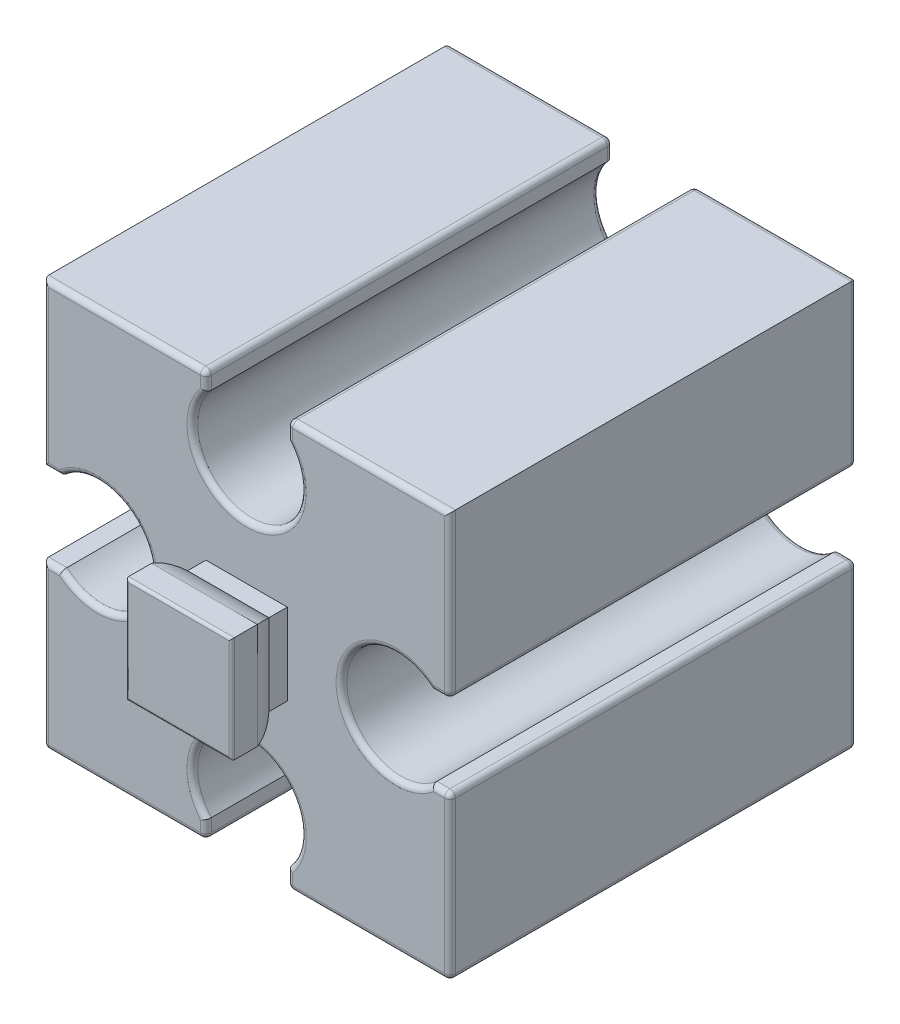
SolidWorks part; units mm, degrees
ref_plane "前视基准面" through (0, 0, 0) normal (0, 0, 1) x (1, 0, 0)
ref_plane "上视基准面" through (0, 0, 0) normal (0, 1, 0) x (1, 0, 0)
ref_plane "右视基准面" through (0, 0, 0) normal (1, 0, 0) x (0, 0, -1)
sketch "草图1" plane through (0, 0, 0) normal (0, 0, 1) x (1, 0, 0)
  line L1 (-7.5, -7.5) -> (7.5, -7.5)
  line L2 (-7.5, -7.5) -> (-7.5, 7.5)
  line L3 (-7.5, 7.5) -> (7.5, 7.5)
  line L4 (7.5, -7.5) -> (7.5, 7.5)
extrude "凸台-拉伸1" add sketch "草图1" against normal blind 15
sketch "草图2" plane through (0, 0, 0) normal (0, 1, 0) x (1, 0, 0)
  line L0 (-7.5, 0) -> (7.5, 0) construction
  line L1 (-1.5, 0) -> (1.5, 0)
  line L2 (-1.5, 0) -> (-1.5, -1)
  line L3 (-1.5, -1) -> (1.5, -1)
  line L4 (1.5, 0) -> (1.5, -1)
extrude "凸台-拉伸2" add sketch "草图2" along normal blind 1.5 and the other way blind 1.5
sketch "草图3" plane through (0, 0, 0) normal (0, 1, 0) x (1, 0, 0)
  line L1 (-1.95, -2.5) -> (1.95, -2.5)
  line L2 (-1.95, -2.5) -> (-1.95, -1.5556)
  line L3 (1.95, -2.5) -> (1.95, -1.5556)
  line L4 (-1.5, 0) -> (-1.5, -1) construction
  line L5 (-1.5, -0.6771) -> (1.5, -0.6771)
  arc A0 (-1.5, -0.6771) -> (-1.95, -1.5556) centre (0, -2) ccw
  arc A1 (1.95, -1.5556) -> (1.5, -0.6771) centre (0, -2) ccw
extrude "凸台-拉伸3" add sketch "草图3" along normal blind 3 and the other way blind 3
sketch "草图5" plane through (0, 0, 0) normal (0, 0, 1) x (1, 0, 0)
  line L0 (-7.5, -7.5) -> (7.5, -7.5) construction
  line L1 (-1.5, -7.5) -> (1.5, -7.5)
  line L2 (-1.5, -7.5) -> (-1.5, -6.8229)
  line L3 (-7.5, 7.5) -> (-7.5, -7.5) construction
  line L4 (1.5, -7.5) -> (1.5, -6.8229)
  line L6 (1.5, 7.5) -> (1.5, 6.8229)
  line L7 (-1.5, 7.5) -> (-1.5, 6.8229)
  line L8 (-1.5, 7.5) -> (1.5, 7.5)
  line L9 (-7.5, 1.5) -> (-6.8229, 1.5)
  line L10 (-7.5, 1.5) -> (-7.5, -1.5)
  line L11 (-7.5, -1.5) -> (-6.8229, -1.5)
  line L12 (7.5, -1.5) -> (6.8229, -1.5)
  line L13 (7.5, 1.5) -> (7.5, -1.5)
  line L14 (7.5, 1.5) -> (6.8229, 1.5)
  arc A0 (1.5, -6.8229) -> (-1.5, -6.8229) centre (0, -5.5) ccw
  arc A1 (1.5, 6.8229) -> (-1.5, 6.8229) centre (0, 5.5) cw
  arc A2 (-6.8229, -1.5) -> (-6.8229, 1.5) centre (-5.5, 0) ccw
  arc A3 (6.8229, -1.5) -> (6.8229, 1.5) centre (5.5, 0) cw
extrude "切除-拉伸2" cut sketch "草图5" against normal through all
sketch "草图12" plane through (0, 0, 0) normal (1, 0, 0) x (0, 0, -1)
  line L0 (-2.5, 3) -> (-2.5, 1.95)
  line L1 (-2.5, 1.95) -> (-1.5556, 1.95)
  line L2 (-2.5, -1.95) -> (-1.5556, -1.95)
  line L5 (-2.5, -1.95) -> (-2.5, -3)
  line L6 (-2.5, 3) -> (-0.6771, 3)
  line L7 (-0.6771, 3) -> (-0.6771, 1.5)
  line L8 (-2.5, -3) -> (-0.6771, -3)
  line L9 (-0.6771, -3) -> (-0.6771, -1.5)
  arc A0 (-0.6771, 1.5) -> (-1.5556, 1.95) centre (-2, 0) ccw
  arc A1 (-1.5556, -1.95) -> (-0.6771, -1.5) centre (-2, 0) ccw
extrude "切除-拉伸7" cut sketch "草图12" against normal up to next and the other way up to next
sketch "草图13" plane through (0, 0, -15) normal (0, 0, -1) x (-1, 0, 0)
  line L1 (-1.5, -1.5) -> (1.5, -1.5)
  line L2 (-1.5, -1.5) -> (-1.5, 1.5)
  line L3 (-1.5, 1.5) -> (1.5, 1.5)
  line L4 (1.5, -1.5) -> (1.5, 1.5)
extrude "凸台-拉伸4" add sketch "草图13" along normal blind 1
sketch "草图14" plane through (0, 0, 0) normal (0, 1, 0) x (1, 0, 0)
  line L0 (-1.95, 17.5) -> (1.95, 17.5)
  line L1 (-1.95, 17.5) -> (-1.95, 16.5556)
  line L2 (1.95, 17.5) -> (1.95, 16.5556)
  line L4 (-1.5, 16) -> (-1.5, 15) construction
  line L5 (-1.5, 15.6771) -> (1.5, 15.6771)
  arc A0 (1.5, 15.6771) -> (1.95, 16.5556) centre (0, 17) ccw
  arc A1 (-1.95, 16.5556) -> (-1.5, 15.6771) centre (0, 17) ccw
extrude "凸台-拉伸5" add sketch "草图14" along normal blind 2 and the other way blind 2
sketch "草图15" plane through (0, 0, 0) normal (1, 0, 0) x (0, 0, -1)
  line L0 (17.5, 2) -> (17.5, 1.95)
  line L1 (17.5, -2) -> (15.6771, -2)
  line L2 (15.6771, -2) -> (15.6771, -1.5)
  line L3 (17.5, 2) -> (15.6771, 2)
  line L4 (15.6771, 2) -> (15.6771, 1.5)
  line L5 (17.5, 1.95) -> (16.5556, 1.95)
  line L6 (17.5, -1.95) -> (16.5556, -1.95)
  line L7 (17.5, -1.95) -> (17.5, -2)
  arc A1 (16.5556, 1.95) -> (15.6771, 1.5) centre (17, 0) ccw
  arc A2 (15.6771, -1.5) -> (16.5556, -1.95) centre (17, 0) ccw
extrude "切除-拉伸8" cut sketch "草图15" against normal up to next and the other way up to next
fillet "圆角2" radius 0.1 8 edges at (-1.95, 0, 2.5) (0, -1.95, 2.5) (1.95, 0, 2.5) (0, 1.95, 2.5) (0, -1.95, -17.5) (1.95, 0, -17.5) (0, 1.95, -17.5) (-1.95, 0, -17.5)
fillet "圆角3" radius 0.2 48 edges at (-4.5, 7.5, -15) (-7.5, 4.5, -15) (-7.1614, 1.5, -15) (-3.5, 0, -15) (-7.1614, -1.5, -15) (-7.5, -4.5, -15) (-4.5, -7.5, -15) (4.5, -7.5, -15) (7.5, -4.5, -15) (7.1614, -1.5, -15) (3.5, 0, -15) (7.1614, 1.5, -15) (7.5, 4.5, -15) (4.5, 7.5, -15) (7.1614, -1.5, 0) (7.5, -4.5, 0) (4.5, -7.5, 0) (1.5, -7.1614, 0) (0, -3.5, 0) (-1.5, -7.1614, 0) (-4.5, -7.5, 0) (-7.5, -4.5, 0) (-7.1614, -1.5, 0) (-3.5, 0, 0) (-7.1614, 1.5, 0) (-7.5, 4.5, 0) (-4.5, 7.5, 0) (-1.5, 7.1614, 0) (0, 3.5, 0) (1.5, 7.1614, 0) (4.5, 7.5, 0) (7.5, 4.5, 0) (7.1614, 1.5, 0) (3.5, 0, 0) (-7.5, -7.5, -7.5) (-1.5, -7.5, -7.5) (1.5, -7.5, -7.5) (7.5, -7.5, -7.5) (1.5, 7.5, -7.5) (-1.5, 7.5, -7.5) (-1.5, -7.1614, -15) (1.5, -7.1614, -15) (0, -3.5, -15) (-1.5, 7.1614, -15) (1.5, 7.1614, -15) (0, 3.5, -15) (7.5, -1.5, -7.5) (7.5, 1.5, -7.5)
